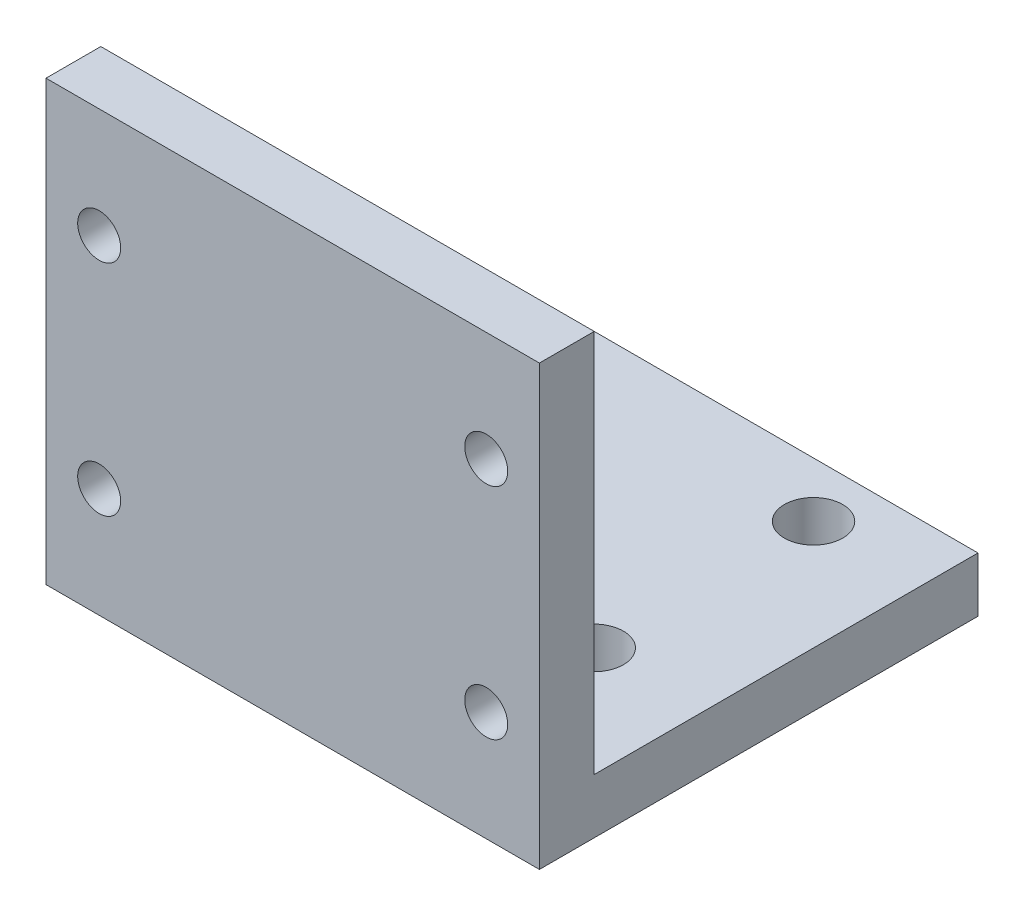
SolidWorks part; units mm, degrees
ref_plane "Front Plane" through (0, 0, 0) normal (0, 0, 1) x (1, 0, 0)
ref_plane "Top Plane" through (0, 0, 0) normal (0, 1, 0) x (1, 0, 0)
ref_plane "Right Plane" through (0, 0, 0) normal (1, 0, 0) x (0, 0, -1)
sketch "Sketch1" plane through (0, 0, 0) normal (1, 0, 0) x (0, 0, -1)
  line L0 (0, 0) -> (0, 50.8)
  line L1 (0, 50.8) -> (6.35, 50.8)
  line L2 (6.35, 50.8) -> (6.35, 6.35)
  line L3 (6.35, 6.35) -> (50.8, 6.35)
  line L4 (50.8, 6.35) -> (50.8, 0)
  line L5 (50.8, 0) -> (0, 0)
  dimension "D1" = 50.8
  dimension "D2" = 50.8
  dimension "D3" = 6.35
  dimension "D4" = 6.35
extrude "Boss-Extrude1" add sketch "Sketch1" along normal blind 57.15
sketch "Sketch3" plane through (0, 0, 0) normal (0, 0, 1) x (1, 0, 0)
  line L0 (0, 38.1) -> (57.15, 38.1) construction
  line L1 (0, 50.8) -> (0, 0) construction
  line L2 (57.15, 50.8) -> (57.15, 0) construction
  line L3 (0, 12.7) -> (57.15, 12.7) construction
  line L4 (6.1595, 38.1) -> (6.1595, 12.7) construction
  line L5 (50.9905, 12.7) -> (50.9905, 38.1) construction
  line L6 (6.1595, 25.4) -> (50.9905, 25.4) construction
  line L7 (28.575, 50.8) -> (28.575, 0) construction
  line L8 (57.15, 50.8) -> (0, 50.8) construction
  line L9 (57.15, 0) -> (0, 0) construction
  circle A0 centre (6.1595, 38.1) radius 2.4892
  circle A1 centre (50.9905, 38.1) radius 2.4892
  circle A2 centre (50.9905, 12.7) radius 2.4892
  circle A3 centre (6.1595, 12.7) radius 2.4892
  point P18 (6.1595, 25.4)
  point P25 (28.575, 25.4)
  dimension "D4" = 4.9784
  dimension "D1" = 25.4
  dimension "D2" = 44.831
  dimension "D3" = 12.7
extrude "Cut-Extrude1" cut sketch "Sketch3" against normal through all
sketch "Sketch4" plane through (0, 6.35, 0) normal (0, 1, 0) x (1, 0, 0)
  line L0 (12.7, 19.05) -> (44.45, 19.05) construction
  line L3 (44.45, 44.45) -> (12.7, 44.45) construction
  line L4 (0, 31.75) -> (57.15, 31.75) construction
  line L5 (28.575, 19.05) -> (28.575, 44.45) construction
  line L7 (57.15, 50.8) -> (57.15, 6.35) construction
  line L8 (0, 50.8) -> (0, 6.35) construction
  line L9 (57.15, 50.8) -> (0, 50.8) construction
  circle A0 centre (12.7, 19.05) radius 3.3782
  circle A1 centre (12.7, 44.45) radius 3.3782
  circle A2 centre (44.45, 44.45) radius 3.3782
  circle A3 centre (44.45, 19.05) radius 3.3782
  point P12 (28.575, 31.75)
  dimension "D3" = 6.7564
  dimension "D1" = 25.4
  dimension "D2" = 31.75
  dimension "D4" = 19.05
extrude "Cut-Extrude2" cut sketch "Sketch4" against normal through all
